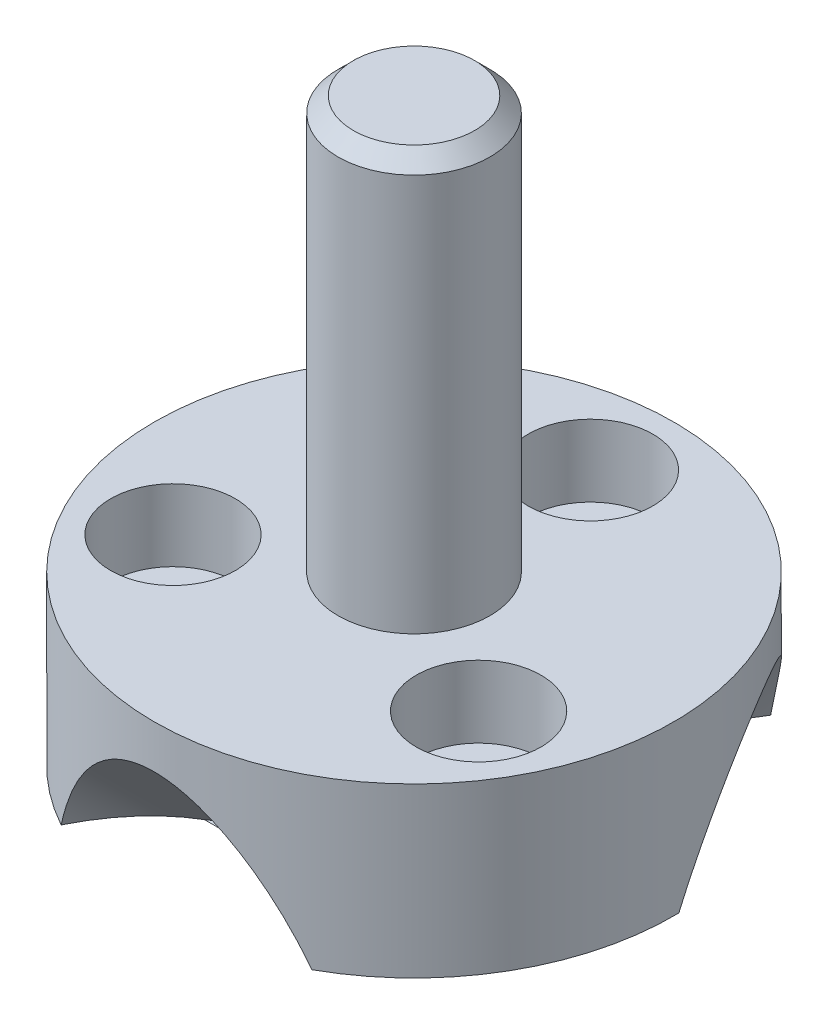
SolidWorks part; units mm, degrees
ref_plane "Front Plane" through (0, 0, 0) normal (0, 0, 1) x (1, 0, 0)
ref_plane "Top Plane" through (0, 0, 0) normal (0, 1, 0) x (1, 0, 0)
ref_plane "Right Plane" through (0, 0, 0) normal (1, 0, 0) x (0, 0, -1)
sketch "Sketch1" plane through (0, 0, 0) normal (0, 1, 0) x (1, 0, 0)
  circle A0 centre (0, 0) radius 8.5
  dimension "D1" = 17
extrude "Boss-Extrude1" add sketch "Sketch1" along normal blind 5.5
sketch "Sketch2" plane through (0, 5.5, 0) normal (0, 1, 0) x (1, 0, 0)
  circle A0 centre (0, 0) radius 2.485
  dimension "D1" = 4.97
extrude "Boss-Extrude2" add sketch "Sketch2" along normal blind 13.5
chamfer "Chamfer1" distance 0.5 angle 45 1 edges at (0, 19, 2.485)
sketch "Sketch5" plane through (0, 0, 0) normal (0, -1, 0) x (1, 0, 0)
  circle A0 centre (0, 0) radius 4.5
  dimension "D1" = 9
extrude "Cut-Extrude3" cut sketch "Sketch5" against normal blind 2.54
sketch "Sketch3" plane through (0, 5.5, 0) normal (0, 1, 0) x (1, 0, 0)
  line L0 (0, 0) -> (0, 8.5) construction
  line L1 (0, 0) -> (7.3612, -4.25) construction
  line L2 (0, 0) -> (-7.3612, -4.25) construction
  circle A0 centre (0, 0) radius 8.5 construction
  circle A1 centre (0, 5.7735) radius 2.04
  circle A2 centre (5, -2.8868) radius 2.04
  circle A3 centre (-5, -2.8868) radius 2.04
  dimension "D1" = 4.08
  dimension "D3" = 10
  dimension "D2" = 3
extrude "Cut-Extrude1" cut sketch "Sketch3" against normal blind 2.35
sketch "Sketch4" plane through (0, 3.15, 0) normal (0, 1, 0) x (1, 0, 0)
  line L0 (-5, -2.8868) -> (0, 0) construction
  line L1 (0, 0) -> (0, 8.5) construction
  circle A0 centre (0, 5.7735) radius 1.065
  circle A1 centre (5, -2.8868) radius 1.065
  circle A2 centre (-5, -2.8868) radius 1.065
  circle A3 centre (0, 0) radius 8.5 construction
  circle A4 centre (0, 0) radius 4.5 construction
  point P3 (-4.0777, -2.3543)
  point P10 (-3.8971, -2.25)
  dimension "D1" = 2.13
  dimension "D3" = 120
  dimension "D2" = 3
extrude "Cut-Extrude2" cut sketch "Sketch4" against normal blind 22.35
ref_plane "Plane1" through (0, 0, 0) normal (0, 0.7071, 0.7071) x (1, 0, 0)
ref_plane "Plane2" through (0, 2.4749, 2.4749) normal (0, 0.7071, 0.7071) x (1, 0, 0)
sketch "Sketch7" plane through (0, 2.4749, 2.4749) normal (0, 0.7071, 0.7071) x (1, 0, 0)
  line L0 (0, 0) -> (0, -8.1213) construction
  circle A0 centre (0, -8.1213) radius 5
  ellipse E0 centre (0, 3.8891) end of major axis (8.5, 3.8891) minor radius 6.0104 construction
  point P4 (0, -3.1213)
  point P5 (0, -2.1213)
  dimension "D1" = 10
  dimension "D2" = 1
extrude "Cut-Extrude5" cut sketch "Sketch7" along normal blind 11.54
pattern_circular "CirPattern1" count 3 over 360 about axis through (0, 0, 0) along (0, 1, 0) of "Cut-Extrude5"
